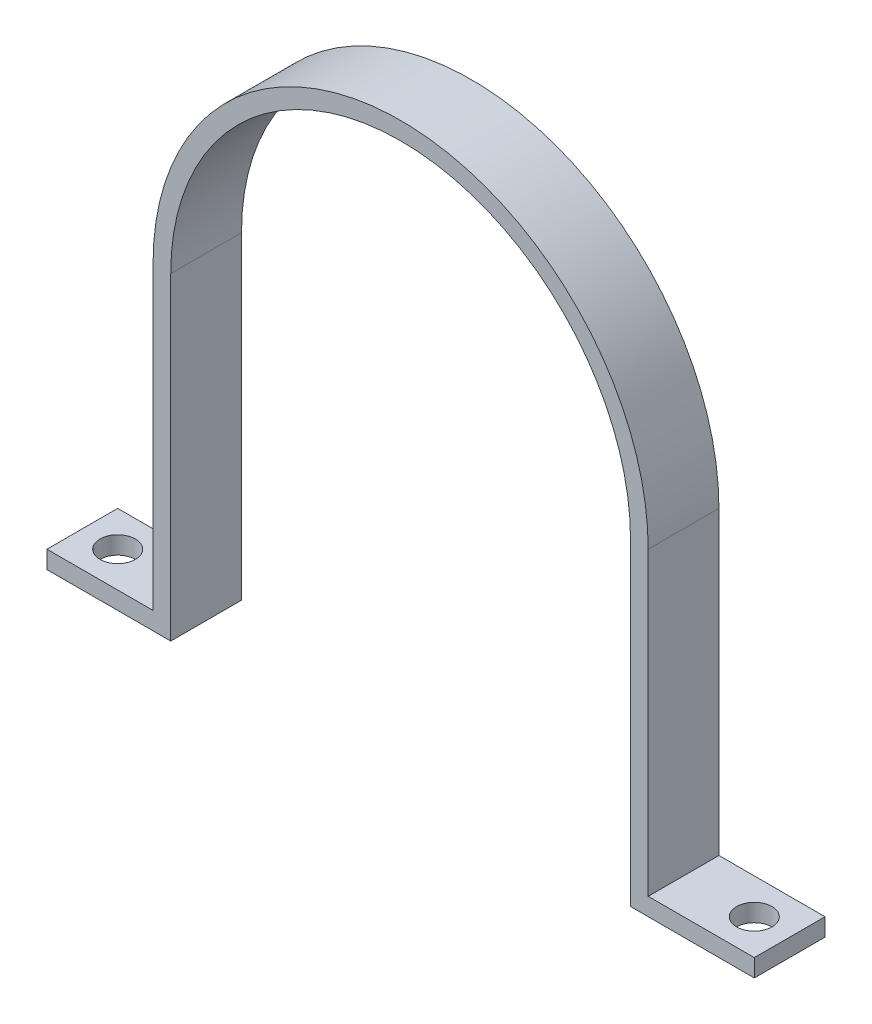
SolidWorks part; units mm, degrees
material "Plain Carbon Steel"
ref_plane "Front Plane" through (0, 0, 0) normal (0, 0, 1) x (1, 0, 0)
ref_plane "Top Plane" through (0, 0, 0) normal (0, 1, 0) x (1, 0, 0)
ref_plane "Right Plane" through (0, 0, 0) normal (1, 0, 0) x (0, 0, -1)
sketch "Sketch7" plane through (0, 0, 0) normal (1, 0, 0) x (0, 0, -1)
  line L0 (-57.5, -23.5) -> (-35.5, -23.5)
  line L1 (-31.5, 0) -> (-31.5, -19.5)
  line L2 (31.5, 0) -> (31.5, -19.5)
  line L4 (35.5, -23.5) -> (57.5, -23.5)
  arc A0 (31.5, 0) -> (-31.5, 0) centre (0, 0) ccw
  arc A1 (-31.5, -19.5) -> (-35.5, -23.5) centre (-35.5, -19.5) cw
  arc A2 (31.5, -19.5) -> (35.5, -23.5) centre (35.5, -19.5) ccw
  point P1 (0, 0)
  point P6 (0, 31.5)
  point P14 (31.5, -23.5)
  dimension "D1" = 63
  dimension "D4" = 4
  dimension "D5" = 4
  dimension "D2" = 115
  dimension "D3" = 55
sketch "Sketch3" plane through (0, 0, 0) normal (0, 0, 1) x (1, 0, 0)
  line L10 (-26, -26) -> (26, -26) construction
  line L12 (-26, 0) -> (-26, -36)
  line L13 (-26, -36) -> (-40, -36)
  line L14 (-40, -34) -> (-40, -36)
  line L16 (26, 0) -> (26, -36)
  line L17 (26, -36) -> (40, -36)
  line L19 (-40, -34) -> (-28, -34)
  line L20 (-28, -34) -> (-28, 0)
  line L21 (28, 0) -> (28, -34)
  line L22 (28, -34) -> (40, -34)
  line L23 (40, -34) -> (40, -36)
  line L24 (-52.6919, -36.2111) -> (-52.5838, -35.995)
  arc A0 (26, 0) -> (-26, 0) centre (0, 0) ccw
  arc A1 (28, 0) -> (-28, 0) centre (0, 0) ccw
  circle A2 centre (0, 0) radius 26 construction
  dimension "D1" = 2
  dimension "D2" = 10
  dimension "D3" = 26
  dimension "D4" = 80
  dimension "D5" = 2
extrude "Boss-Extrude1" add sketch "Sketch3" along normal blind 8 contours L21 A1 L20 L19 L14 L13 L12 A0 L16 L17 L23 L22
hole_wizard "Tap Drill for M4x0.7 Tap1" positions "Sketch5" profile "Sketch6" hole size "M4x0.7" standard "ANSI Metric" end condition through all
sketch "Sketch5" plane through (0, -34, 0) normal (0, 1, 0) x (1, 0, 0)
  line L2 (-40, 0) -> (-28, 0) construction
  line L4 (-40, -8) -> (-40, 0) construction
  line L6 (40, -8) -> (40, 0) construction
  point P0 (-36, -4)
  point P2 (36, -4)
  dimension "D1" = 4
  dimension "D2" = 4
  dimension "D3" = 4
sketch "Sketch6" plane through (-36, -34, 4) normal (1, 0, 0) x (0, 0, 1)
  line L0 (0, 0) -> (0, 2)
  line L1 (0, 2) -> (1.65, 2)
  line L2 (1.65, 2) -> (1.65, 0)
  line L5 (1.65, 0) -> (0, 0)
  line L11 (0, -6.35) -> (0, 107.95) construction
  dimension "Thru Hole Dia." = 3.3
  dimension "Thru Hole Depth" = 2
sketch "Sketch4" plane through (0, -34, 0) normal (0, 1, 0) x (1, 0, 0)
  line L0 (-40, 0) -> (-28, 0) construction
  line L1 (-40, -8) -> (-40, 0) construction
  line L2 (40, -8) -> (40, 0) construction
  circle A0 centre (-36, -4) radius 2
  circle A1 centre (36, -4) radius 2
  dimension "D1" = 4
  dimension "D2" = 4
  dimension "D3" = 4
  dimension "D4" = 4
extrude "Cut-Extrude1" cut sketch "Sketch4" against normal through all
